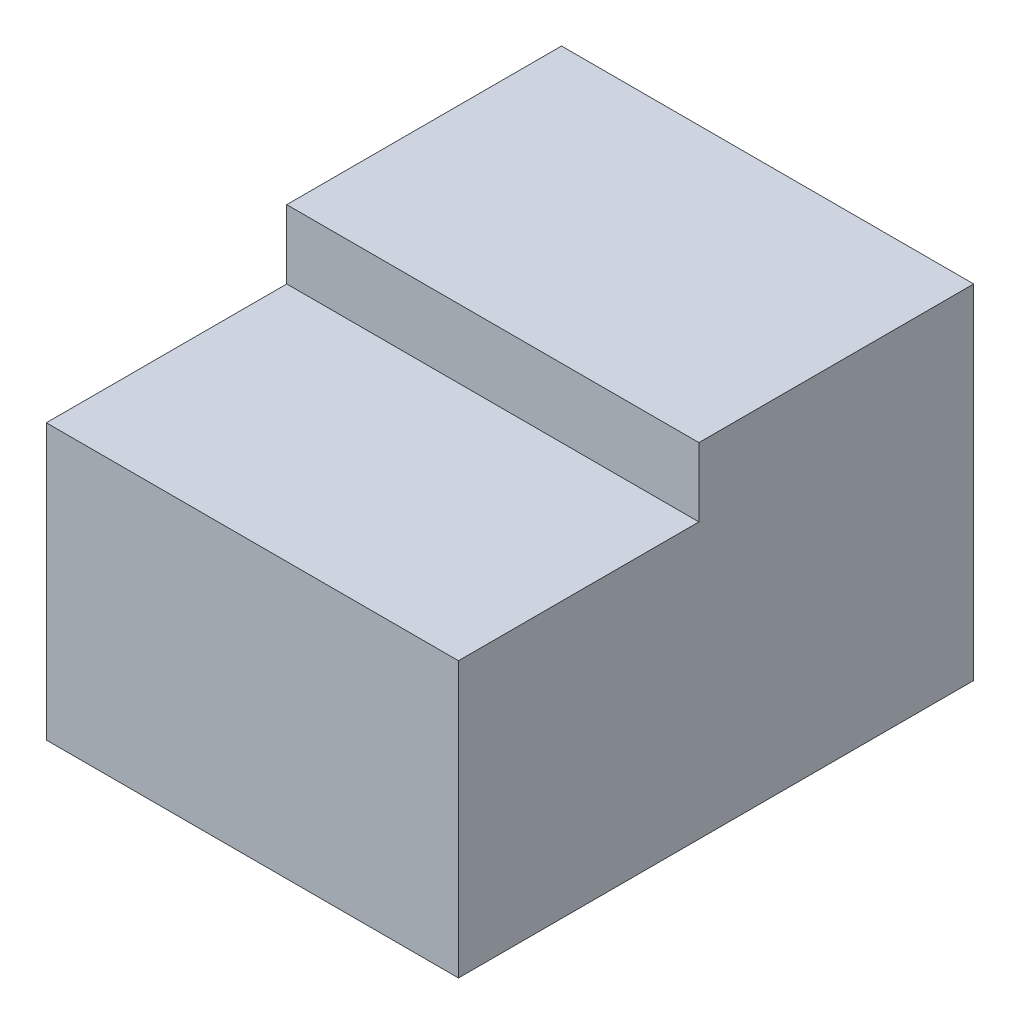
SolidWorks part; units mm, degrees
ref_plane "Front Plane" through (0, 0, 0) normal (0, 0, 1) x (1, 0, 0)
ref_plane "Top Plane" through (0, 0, 0) normal (0, 1, 0) x (1, 0, 0)
ref_plane "Right Plane" through (0, 0, 0) normal (1, 0, 0) x (0, 0, -1)
sketch "Sketch2" plane through (0, 0, 0) normal (1, 0, 0) x (0, 0, -1)
  line L0 (0, 0) -> (-15, 0)
  line L1 (-15, 0) -> (-15, 8)
  line L2 (-15, 8) -> (-8, 8)
  line L3 (-8, 8) -> (-8, 10)
  line L4 (-8, 10) -> (0, 10)
  line L5 (0, 10) -> (0, 0)
  dimension "D1" = 15
  dimension "D2" = 8
  dimension "D3" = 10
  dimension "D4" = 8
extrude "Boss-Extrude1" add sketch "Sketch2" along normal blind 12 contours L0 L1 L2 L3 L4 L5
sketch "Sketch3" plane through (0, 0, 0) normal (0, 0, -1) x (-1, 0, 0)
  line L0 (-12, 10) -> (-12, 0) construction
  line L1 (-12, 10) -> (0, 10) construction
  line L2 (-4.4123, 7.75) -> (-7.5877, 7.75)
  line L3 (-7.5877, 7.75) -> (-9.1754, 5)
  line L4 (-9.1754, 5) -> (-7.5877, 2.25)
  line L5 (-7.5877, 2.25) -> (-4.4123, 2.25)
  line L6 (-4.4123, 2.25) -> (-2.8246, 5)
  line L7 (-2.8246, 5) -> (-4.4123, 7.75)
  circle A0 centre (-6, 5) radius 3.1754 construction
  dimension "D1" = 6
  dimension "D2" = 5
  dimension "D3" = 5.5
  dimension "D4" = 5.5
extrude "Cut-Extrude1" cut sketch "Sketch3" against normal blind 5
sketch "Sketch4" plane through (0, 0, 0) normal (0, -1, 0) x (1, 0, 0)
  line L0 (12, 0) -> (12, 15) construction
  line L2 (12, 15) -> (0, 15) construction
  line L3 (4.4123, 7.25) -> (7.5877, 7.25)
  line L4 (7.5877, 7.25) -> (9.1754, 10)
  line L5 (9.1754, 10) -> (7.5877, 12.75)
  line L6 (7.5877, 12.75) -> (4.4123, 12.75)
  line L7 (4.4123, 12.75) -> (2.8246, 10)
  line L8 (2.8246, 10) -> (4.4123, 7.25)
  circle A0 centre (6, 10) radius 3.1754 construction
  dimension "D1" = 6
  dimension "D2" = 5
  dimension "D3" = 5.5
  dimension "D4" = 5.5
extrude "Cut-Extrude2" cut sketch "Sketch4" against normal blind 5
